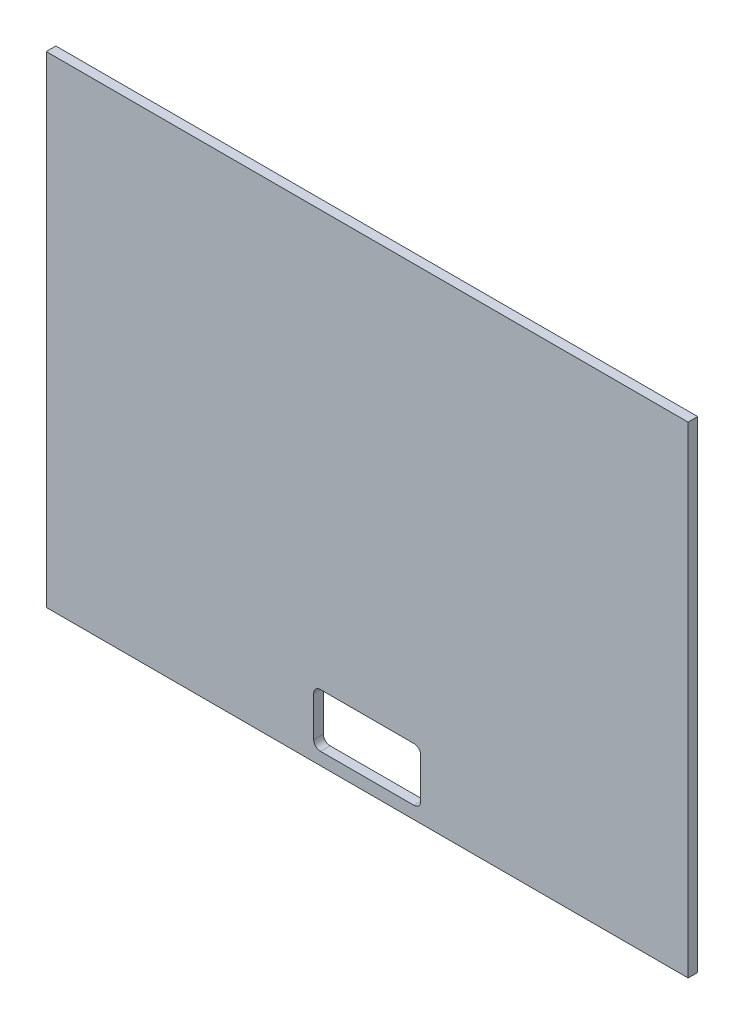
SolidWorks part; units mm, degrees
ref_plane "Front Plane" through (0, 0, 0) normal (0, 0, 1) x (1, 0, 0)
ref_plane "Top Plane" through (0, 0, 0) normal (0, 1, 0) x (1, 0, 0)
ref_plane "Right Plane" through (0, 0, 0) normal (1, 0, 0) x (0, 0, -1)
sketch "Sketch1" plane through (0, 0, 0) normal (0, 0, 1) x (1, 0, 0)
  line L1 (-406.4, -457.2) -> (812.8, -457.2)
  line L2 (-406.4, -457.2) -> (-406.4, 457.2)
  line L3 (-406.4, 457.2) -> (812.8, 457.2)
  line L4 (812.8, -457.2) -> (812.8, 457.2)
  point P0 (0, 0)
  dimension "D1" = 1219.2
  dimension "D2" = 914.4
extrude "Boss-Extrude1" add sketch "Sketch1" along normal blind 18.2562
sketch "Sketch2" plane through (0, 0, 18.2562) normal (0, 0, 1) x (1, 0, 0)
  line L0 (203.2, 457.2) -> (203.2, -457.2) construction
  line L1 (812.8, 457.2) -> (-406.4, 457.2) construction
  line L2 (-406.4, -457.2) -> (812.8, -457.2) construction
  line L3 (-406.4, 457.2) -> (-406.4, -457.2) construction
  line L4 (304.8, -433.4996) -> (101.6, -433.4996)
  line L5 (304.8, -433.4996) -> (304.8, -331.8996)
  line L6 (304.8, -331.8996) -> (101.6, -331.8996)
  line L7 (101.6, -433.4996) -> (101.6, -331.8996)
  line L8 (304.8, -433.4996) -> (101.6, -331.8996) construction
  line L9 (304.8, -331.8996) -> (101.6, -433.4996) construction
  point P6 (203.2, -382.6996)
  dimension "D1" = 101.6
  dimension "D2" = 203.2
extrude "Cut-Extrude1" cut sketch "Sketch2" against normal through all
fillet "Fillet1" radius 12.7 4 edges at (304.8, -433.4996, 9.1281) (101.6, -433.4996, 9.1281) (101.6, -331.8996, 9.1281) (304.8, -331.8996, 9.1281)
